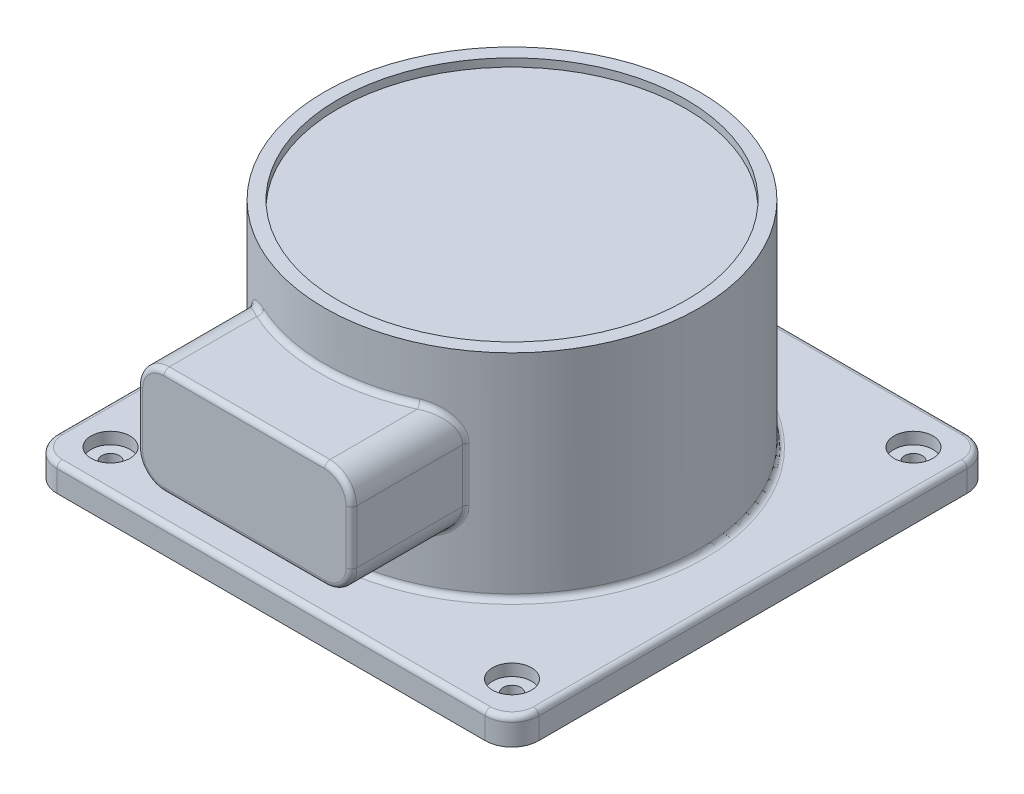
SolidWorks part; units mm, degrees
ref_plane "Front Plane" through (0, 0, 0) normal (0, 0, 1) x (1, 0, 0)
ref_plane "Top Plane" through (0, 0, 0) normal (0, 1, 0) x (1, 0, 0)
ref_plane "Right Plane" through (0, 0, 0) normal (1, 0, 0) x (0, 0, -1)
sketch "Sketch4" plane through (0, 0, 0) normal (0, 1, 0) x (1, 0, 0)
  line L1 (-90, -90) -> (90, -90)
  line L2 (-90, -90) -> (-90, 90)
  line L3 (-90, 90) -> (90, 90)
  line L4 (90, -90) -> (90, 90)
  line L5 (-90, -90) -> (90, 90) construction
  line L6 (-90, 90) -> (90, -90) construction
  point P0 (0, 0)
  dimension "D1" = 180
extrude "Boss-Extrude2" add sketch "Sketch4" along normal blind 10
sketch "Sketch5" plane through (0, 10, 0) normal (0, 1, 0) x (1, 0, 0)
  circle A0 centre (0, 0) radius 70
  dimension "D1" = 140
extrude "Boss-Extrude3" add sketch "Sketch5" along normal blind 80
sketch "Sketch6" plane through (0, 0, 0) normal (0, 0, 1) x (1, 0, 0)
  line L1 (40, 70) -> (-40, 70)
  line L2 (40, 70) -> (40, 30)
  line L3 (40, 30) -> (-40, 30)
  line L4 (-40, 70) -> (-40, 30)
  line L5 (40, 70) -> (-40, 30) construction
  line L6 (40, 30) -> (-40, 70) construction
  point P0 (0, 50)
  dimension "D1" = 40
  dimension "D2" = 80
  dimension "D3" = 50
extrude "Boss-Extrude4" add sketch "Sketch6" along normal blind 100
sketch "Sketch7" plane through (0, 90, 0) normal (0, 1, 0) x (1, 0, 0)
  circle A2 centre (0, 0) radius 65
  circle A3 centre (0, 0) radius 65
  dimension "D1" = 5
extrude "Cut-Extrude1" cut sketch "Sketch7" against normal blind 3
hole_wizard "CBORE for M6 Hex Head Bolt2" positions "Sketch12" profile "Sketch13" counterbore size "M6" standard "ANSI Metric" end condition through all
sketch "Sketch12" plane through (0, 10, 0) normal (0, 1, 0) x (1, 0, 0)
  point P0 (-75, 75)
  point P2 (75, 75)
  point P4 (75, -75)
  point P6 (-75, -75)
  dimension "D1" = 150
  dimension "D2" = 150
  dimension "D3" = 150
  dimension "D4" = 75
  dimension "D5" = 75
sketch "Sketch13" plane through (-75, 10, -75) normal (1, 0, 0) x (0, 0, 1)
  line L0 (0, 0) -> (0, 10)
  line L1 (0, 10) -> (3.3, 10)
  line L3 (3.3, 10) -> (3.3, 4.38)
  line L4 (3.3, 4.38) -> (7.275, 4.38)
  line L5 (7.275, 4.38) -> (7.275, 0)
  line L7 (7.275, 0) -> (0, 0)
  line L11 (0, -6.35) -> (0, 107.95) construction
  dimension "Thru Hole Dia." = 6.6
  dimension "Thru Hole Depth" = 10
  dimension "C'Bore Dia." = 14.55
  dimension "C'Bore Depth" = 4.38
fillet "Fillet1" radius 10 4 edges at (90, 5, 90) (-90, 5, -90) (90, 5, -90) (-90, 5, 90)
fillet "Fillet2" radius 10 4 edges at (-40, 30, 78.7228) (40, 30, 78.7228) (-40, 70, 78.7228) (40, 70, 78.7228)
fillet "Fillet3" radius 2 25 edges at (37.0711, 67.0711, 100) (40, 50, 100) (37.0711, 32.9289, 100) (0, 30, 100) (-37.0711, 32.9289, 100) (-40, 50, 100) (-37.0711, 67.0711, 100) (36.8398, 67.295, 59.5217) (40, 50, 57.4456) (38.3695, 34.5271, 58.5473) (0, 30, 70) (-36.8398, 32.705, 59.5217) (-40, 50, 57.4456) (-38.3695, 65.4729, 58.5473) (-87.0711, 10, 87.0711) (-90, 10, 0) (-87.0711, 10, -87.0711) (0, 10, -90) (87.0711, 10, -87.0711) (90, 10, 0) (87.0711, 10, 87.0711) (0, 70, 100) (0, 10, 70) (0, 70, 70) (0, 10, 90)
